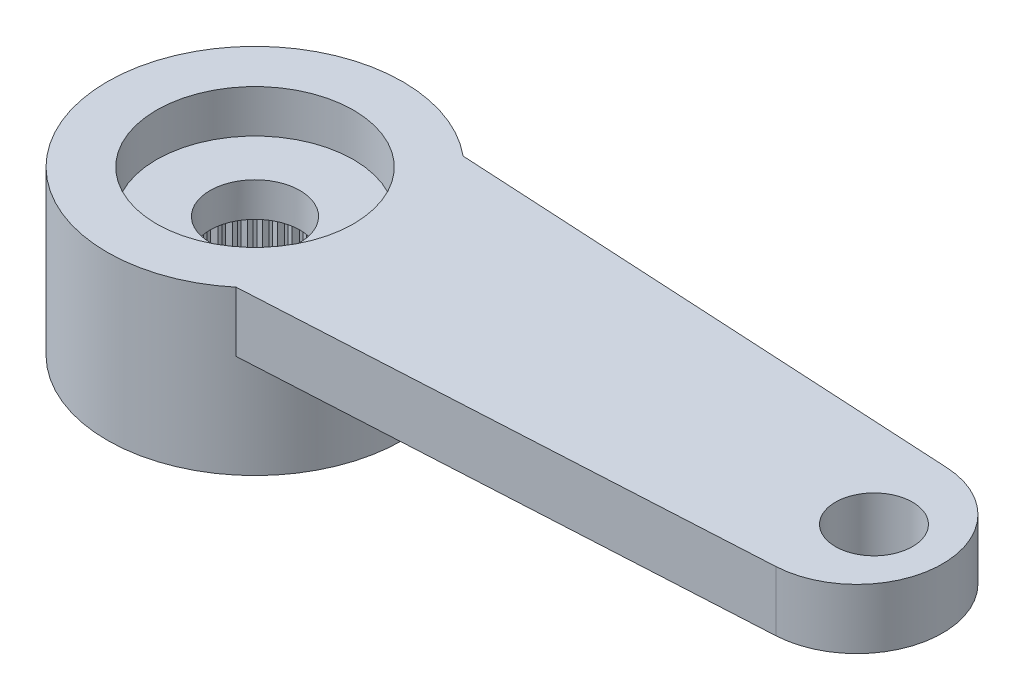
SolidWorks part; units mm, degrees
ref_plane "Front Plane" through (0, 0, 0) normal (0, 0, 1) x (1, 0, 0)
ref_plane "Top Plane" through (0, 0, 0) normal (0, 1, 0) x (1, 0, 0)
ref_plane "Right Plane" through (0, 0, 0) normal (1, 0, 0) x (0, 0, -1)
sketch "Sketch1" plane through (0, 0, 0) normal (0, 1, 0) x (1, 0, 0)
  line L0 (2.2091, -2.65) -> (14.1591, -1.997)
  line L1 (14.1591, 1.997) -> (2.2091, 2.65)
  line L2 (-2.2091, 2.65) -> (-14.1591, 1.997)
  line L3 (-14.1591, -1.997) -> (-2.2091, -2.65)
  arc A0 (-2.2091, -2.65) -> (2.2091, -2.65) centre (0, 0) ccw
  arc A1 (14.1591, -1.997) -> (14.1591, 1.997) centre (14.05, 0) ccw
  arc A2 (2.2091, 2.65) -> (-2.2091, 2.65) centre (0, 0) ccw
  arc A3 (-14.1591, 1.997) -> (-14.1591, -1.997) centre (-14.05, 0) ccw
extrude "Boss-Extrude1" add sketch "Sketch1" against normal blind 1.4
sketch "Sketch2" plane through (0, -1.4, 0) normal (0, -1, 0) x (1, 0, 0)
  circle A0 centre (0, 0) radius 3.45
extrude "Boss-Extrude2" add sketch "Sketch2" along normal blind 2.4
sketch "Sketch3" plane through (0, -3.8, 0) normal (0, -1, 0) x (1, 0, 0)
  line L0 (-0.161, 2.4698) -> (-0.2483, 2.362)
  line L1 (-0.2483, 2.362) -> (-0.356, 2.4493)
  line L2 (-0.4183, 2.4394) -> (-0.4938, 2.3231)
  line L3 (-0.4938, 2.3231) -> (-0.6101, 2.3986)
  line L4 (-0.671, 2.3823) -> (-0.7339, 2.2588)
  line L5 (-0.7339, 2.2588) -> (-0.8575, 2.3217)
  line L6 (-0.9163, 2.2991) -> (-0.966, 2.1697)
  line L7 (-0.966, 2.1697) -> (-1.0955, 2.2194)
  line L8 (-1.1516, 2.1908) -> (-1.1875, 2.0568)
  line L9 (-1.1875, 2.0568) -> (-1.3214, 2.0927)
  line L10 (-1.3743, 2.0584) -> (-1.396, 1.9214)
  line L11 (-1.396, 1.9214) -> (-1.533, 1.9431)
  line L12 (-1.5819, 1.9035) -> (-1.5892, 1.765)
  line L13 (-1.5892, 1.765) -> (-1.7277, 1.7722)
  line L14 (-1.7722, 1.7277) -> (-1.765, 1.5892)
  line L15 (-1.765, 1.5892) -> (-1.9035, 1.5819)
  line L16 (-1.9431, 1.533) -> (-1.9214, 1.396)
  line L17 (-1.9214, 1.396) -> (-2.0584, 1.3743)
  line L18 (-2.0927, 1.3214) -> (-2.0568, 1.1875)
  line L19 (-2.0568, 1.1875) -> (-2.1908, 1.1516)
  line L20 (-2.2194, 1.0955) -> (-2.1697, 0.966)
  line L21 (-2.1697, 0.966) -> (-2.2991, 0.9163)
  line L22 (-2.3217, 0.8575) -> (-2.2588, 0.7339)
  line L23 (-2.2588, 0.7339) -> (-2.3823, 0.671)
  line L24 (-2.3986, 0.6101) -> (-2.3231, 0.4938)
  line L25 (-2.3231, 0.4938) -> (-2.4394, 0.4183)
  line L26 (-2.4493, 0.356) -> (-2.362, 0.2483)
  line L27 (-2.362, 0.2483) -> (-2.4698, 0.161)
  line L28 (-2.4731, 0.0981) -> (-2.375, 0)
  line L29 (-2.375, 0) -> (-2.4731, -0.0981)
  line L30 (-2.4698, -0.161) -> (-2.362, -0.2483)
  line L31 (-2.362, -0.2483) -> (-2.4493, -0.356)
  line L32 (-2.4394, -0.4183) -> (-2.3231, -0.4938)
  line L33 (-2.3231, -0.4938) -> (-2.3986, -0.6101)
  line L34 (-2.3823, -0.671) -> (-2.2588, -0.7339)
  line L35 (-2.2588, -0.7339) -> (-2.3217, -0.8575)
  line L36 (-2.2991, -0.9163) -> (-2.1697, -0.966)
  line L37 (-2.1697, -0.966) -> (-2.2194, -1.0955)
  line L38 (-2.1908, -1.1516) -> (-2.0568, -1.1875)
  line L39 (-2.0568, -1.1875) -> (-2.0927, -1.3214)
  line L40 (-2.0584, -1.3743) -> (-1.9214, -1.396)
  line L41 (-1.9214, -1.396) -> (-1.9431, -1.533)
  line L42 (-1.9035, -1.5819) -> (-1.765, -1.5892)
  line L43 (-1.765, -1.5892) -> (-1.7722, -1.7277)
  line L44 (-1.7277, -1.7722) -> (-1.5892, -1.765)
  line L45 (-1.5892, -1.765) -> (-1.5819, -1.9035)
  line L46 (-1.533, -1.9431) -> (-1.396, -1.9214)
  line L47 (-1.396, -1.9214) -> (-1.3743, -2.0584)
  line L48 (-1.3214, -2.0927) -> (-1.1875, -2.0568)
  line L49 (-1.1875, -2.0568) -> (-1.1516, -2.1908)
  line L50 (-1.0955, -2.2194) -> (-0.966, -2.1697)
  line L51 (-0.966, -2.1697) -> (-0.9163, -2.2991)
  line L52 (-0.8575, -2.3217) -> (-0.7339, -2.2588)
  line L53 (-0.7339, -2.2588) -> (-0.671, -2.3823)
  line L54 (-0.6101, -2.3986) -> (-0.4938, -2.3231)
  line L55 (-0.4938, -2.3231) -> (-0.4183, -2.4394)
  line L56 (-0.356, -2.4493) -> (-0.2483, -2.362)
  line L57 (-0.2483, -2.362) -> (-0.161, -2.4698)
  line L58 (-0.0981, -2.4731) -> (0, -2.375)
  line L59 (0, -2.375) -> (0.0981, -2.4731)
  line L60 (0.161, -2.4698) -> (0.2483, -2.362)
  line L61 (0.2483, -2.362) -> (0.356, -2.4493)
  line L62 (0.4183, -2.4394) -> (0.4938, -2.3231)
  line L63 (0.4938, -2.3231) -> (0.6101, -2.3986)
  line L64 (0.671, -2.3823) -> (0.7339, -2.2588)
  line L65 (0.7339, -2.2588) -> (0.8575, -2.3217)
  line L66 (0.9163, -2.2991) -> (0.966, -2.1697)
  line L67 (0.966, -2.1697) -> (1.0955, -2.2194)
  line L68 (1.1516, -2.1908) -> (1.1875, -2.0568)
  line L69 (1.1875, -2.0568) -> (1.3214, -2.0927)
  line L70 (1.3743, -2.0584) -> (1.396, -1.9214)
  line L71 (1.396, -1.9214) -> (1.533, -1.9431)
  line L72 (1.5819, -1.9035) -> (1.5892, -1.765)
  line L73 (1.5892, -1.765) -> (1.7277, -1.7722)
  line L74 (1.7722, -1.7277) -> (1.765, -1.5892)
  line L75 (1.765, -1.5892) -> (1.9035, -1.5819)
  line L76 (1.9431, -1.533) -> (1.9214, -1.396)
  line L77 (1.9214, -1.396) -> (2.0584, -1.3743)
  line L78 (2.0927, -1.3214) -> (2.0568, -1.1875)
  line L79 (2.0568, -1.1875) -> (2.1908, -1.1516)
  line L80 (2.2194, -1.0955) -> (2.1697, -0.966)
  line L81 (2.1697, -0.966) -> (2.2991, -0.9163)
  line L82 (2.3217, -0.8575) -> (2.2588, -0.7339)
  line L83 (2.2588, -0.7339) -> (2.3823, -0.671)
  line L84 (2.3986, -0.6101) -> (2.3231, -0.4938)
  line L85 (2.3231, -0.4938) -> (2.4394, -0.4183)
  line L86 (2.4493, -0.356) -> (2.362, -0.2483)
  line L87 (2.362, -0.2483) -> (2.4698, -0.161)
  line L88 (2.4731, -0.0981) -> (2.375, 0)
  line L89 (2.375, 0) -> (2.4731, 0.0981)
  line L90 (2.4698, 0.161) -> (2.362, 0.2483)
  line L91 (2.362, 0.2483) -> (2.4493, 0.356)
  line L92 (2.4394, 0.4183) -> (2.3231, 0.4938)
  line L93 (2.3231, 0.4938) -> (2.3986, 0.6101)
  line L94 (2.3823, 0.671) -> (2.2588, 0.7339)
  line L95 (2.2588, 0.7339) -> (2.3217, 0.8575)
  line L96 (2.2991, 0.9163) -> (2.1697, 0.966)
  line L97 (2.1697, 0.966) -> (2.2194, 1.0955)
  line L98 (2.1908, 1.1516) -> (2.0568, 1.1875)
  line L99 (2.0568, 1.1875) -> (2.0927, 1.3214)
  line L100 (2.0584, 1.3743) -> (1.9214, 1.396)
  line L101 (1.9214, 1.396) -> (1.9431, 1.533)
  line L102 (1.9035, 1.5819) -> (1.765, 1.5892)
  line L103 (1.765, 1.5892) -> (1.7722, 1.7277)
  line L104 (1.7277, 1.7722) -> (1.5892, 1.765)
  line L105 (1.5892, 1.765) -> (1.5819, 1.9035)
  line L106 (1.533, 1.9431) -> (1.396, 1.9214)
  line L107 (1.396, 1.9214) -> (1.3743, 2.0584)
  line L108 (1.3214, 2.0927) -> (1.1875, 2.0568)
  line L109 (1.1875, 2.0568) -> (1.1516, 2.1908)
  line L110 (1.0955, 2.2194) -> (0.966, 2.1697)
  line L111 (0.966, 2.1697) -> (0.9163, 2.2991)
  line L112 (0.8575, 2.3217) -> (0.7339, 2.2588)
  line L113 (0.7339, 2.2588) -> (0.671, 2.3823)
  line L114 (0.6101, 2.3986) -> (0.4938, 2.3231)
  line L115 (0.4938, 2.3231) -> (0.4183, 2.4394)
  line L116 (0.356, 2.4493) -> (0.2483, 2.362)
  line L117 (0.2483, 2.362) -> (0.161, 2.4698)
  line L118 (0.0981, 2.4731) -> (0, 2.375)
  line L119 (0, 2.375) -> (-0.0981, 2.4731)
  arc A0 (-0.0981, 2.4731) -> (-0.161, 2.4698) centre (0, 0) ccw
  arc A1 (-0.356, 2.4493) -> (-0.4183, 2.4394) centre (0, 0) ccw
  arc A2 (-0.6101, 2.3986) -> (-0.671, 2.3823) centre (0, 0) ccw
  arc A3 (-0.8575, 2.3217) -> (-0.9163, 2.2991) centre (0, 0) ccw
  arc A4 (-1.0955, 2.2194) -> (-1.1516, 2.1908) centre (0, 0) ccw
  arc A5 (-1.3214, 2.0927) -> (-1.3743, 2.0584) centre (0, 0) ccw
  arc A6 (-1.533, 1.9431) -> (-1.5819, 1.9035) centre (0, 0) ccw
  arc A7 (-1.7277, 1.7722) -> (-1.7722, 1.7277) centre (0, 0) ccw
  arc A8 (-1.9035, 1.5819) -> (-1.9431, 1.533) centre (0, 0) ccw
  arc A9 (-2.0584, 1.3743) -> (-2.0927, 1.3214) centre (0, 0) ccw
  arc A10 (-2.1908, 1.1516) -> (-2.2194, 1.0955) centre (0, 0) ccw
  arc A11 (-2.2991, 0.9163) -> (-2.3217, 0.8575) centre (0, 0) ccw
  arc A12 (-2.3823, 0.671) -> (-2.3986, 0.6101) centre (0, 0) ccw
  arc A13 (-2.4394, 0.4183) -> (-2.4493, 0.356) centre (0, 0) ccw
  arc A14 (-2.4698, 0.161) -> (-2.4731, 0.0981) centre (0, 0) ccw
  arc A15 (-2.4731, -0.0981) -> (-2.4698, -0.161) centre (0, 0) ccw
  arc A16 (-2.4493, -0.356) -> (-2.4394, -0.4183) centre (0, 0) ccw
  arc A17 (-2.3986, -0.6101) -> (-2.3823, -0.671) centre (0, 0) ccw
  arc A18 (-2.3217, -0.8575) -> (-2.2991, -0.9163) centre (0, 0) ccw
  arc A19 (-2.2194, -1.0955) -> (-2.1908, -1.1516) centre (0, 0) ccw
  arc A20 (-2.0927, -1.3214) -> (-2.0584, -1.3743) centre (0, 0) ccw
  arc A21 (-1.9431, -1.533) -> (-1.9035, -1.5819) centre (0, 0) ccw
  arc A22 (-1.7722, -1.7277) -> (-1.7277, -1.7722) centre (0, 0) ccw
  arc A23 (-1.5819, -1.9035) -> (-1.533, -1.9431) centre (0, 0) ccw
  arc A24 (-1.3743, -2.0584) -> (-1.3214, -2.0927) centre (0, 0) ccw
  arc A25 (-1.1516, -2.1908) -> (-1.0955, -2.2194) centre (0, 0) ccw
  arc A26 (-0.9163, -2.2991) -> (-0.8575, -2.3217) centre (0, 0) ccw
  arc A27 (-0.671, -2.3823) -> (-0.6101, -2.3986) centre (0, 0) ccw
  arc A28 (-0.4183, -2.4394) -> (-0.356, -2.4493) centre (0, 0) ccw
  arc A29 (-0.161, -2.4698) -> (-0.0981, -2.4731) centre (0, 0) ccw
  arc A30 (0.0981, -2.4731) -> (0.161, -2.4698) centre (0, 0) ccw
  arc A31 (0.356, -2.4493) -> (0.4183, -2.4394) centre (0, 0) ccw
  arc A32 (0.6101, -2.3986) -> (0.671, -2.3823) centre (0, 0) ccw
  arc A33 (0.8575, -2.3217) -> (0.9163, -2.2991) centre (0, 0) ccw
  arc A34 (1.0955, -2.2194) -> (1.1516, -2.1908) centre (0, 0) ccw
  arc A35 (1.3214, -2.0927) -> (1.3743, -2.0584) centre (0, 0) ccw
  arc A36 (1.533, -1.9431) -> (1.5819, -1.9035) centre (0, 0) ccw
  arc A37 (1.7277, -1.7722) -> (1.7722, -1.7277) centre (0, 0) ccw
  arc A38 (1.9035, -1.5819) -> (1.9431, -1.533) centre (0, 0) ccw
  arc A39 (2.0584, -1.3743) -> (2.0927, -1.3214) centre (0, 0) ccw
  arc A40 (2.1908, -1.1516) -> (2.2194, -1.0955) centre (0, 0) ccw
  arc A41 (2.2991, -0.9163) -> (2.3217, -0.8575) centre (0, 0) ccw
  arc A42 (2.3823, -0.671) -> (2.3986, -0.6101) centre (0, 0) ccw
  arc A43 (2.4394, -0.4183) -> (2.4493, -0.356) centre (0, 0) ccw
  arc A44 (2.4698, -0.161) -> (2.4731, -0.0981) centre (0, 0) ccw
  arc A45 (2.4731, 0.0981) -> (2.4698, 0.161) centre (0, 0) ccw
  arc A46 (2.4493, 0.356) -> (2.4394, 0.4183) centre (0, 0) ccw
  arc A47 (2.3986, 0.6101) -> (2.3823, 0.671) centre (0, 0) ccw
  arc A48 (2.3217, 0.8575) -> (2.2991, 0.9163) centre (0, 0) ccw
  arc A49 (2.2194, 1.0955) -> (2.1908, 1.1516) centre (0, 0) ccw
  arc A50 (2.0927, 1.3214) -> (2.0584, 1.3743) centre (0, 0) ccw
  arc A51 (1.9431, 1.533) -> (1.9035, 1.5819) centre (0, 0) ccw
  arc A52 (1.7722, 1.7277) -> (1.7277, 1.7722) centre (0, 0) ccw
  arc A53 (1.5819, 1.9035) -> (1.533, 1.9431) centre (0, 0) ccw
  arc A54 (1.3743, 2.0584) -> (1.3214, 2.0927) centre (0, 0) ccw
  arc A55 (1.1516, 2.1908) -> (1.0955, 2.2194) centre (0, 0) ccw
  arc A56 (0.9163, 2.2991) -> (0.8575, 2.3217) centre (0, 0) ccw
  arc A57 (0.671, 2.3823) -> (0.6101, 2.3986) centre (0, 0) ccw
  arc A58 (0.4183, 2.4394) -> (0.356, 2.4493) centre (0, 0) ccw
  arc A59 (0.161, 2.4698) -> (0.0981, 2.4731) centre (0, 0) ccw
extrude "Cut-Extrude1" cut sketch "Sketch3" against normal blind 2
hole_wizard "Hole1" positions "Sketch5" profile "Sketch4" legacy
sketch "Sketch5" plane through (0, 0, 0) normal (0, 1, 0) x (1, 0, 0)
  point P0 (0, 0)
sketch "Sketch4" plane through (0, 0, 0) normal (1, 0, 0) x (0, 0, 1)
  line L0 (0, 0) -> (0, 3.8)
  line L1 (0, 3.8) -> (1.05, 3.8)
  line L2 (1.05, 3.8) -> (1.05, 1)
  line L3 (1.05, 1) -> (2.3, 1)
  line L4 (2.3, 1) -> (2.3, 0)
  line L5 (2.3, 0) -> (0, 0)
  line L6 (0, 110) -> (0, -10) construction
  dimension "Diameter" = 2.1
  dimension "Depth" = 3.8
  dimension "C-Bore Diameter" = 4.6
  dimension "C-Bore Depth" = 1
sketch "Sketch6" plane through (0, 0, 0) normal (0, 1, 0) x (1, 0, 0)
  line L3 (-14.1591, -1.997) -> (-2.2091, -2.65)
  line L4 (-2.2091, 2.65) -> (-2.124, 2.7652)
  line L5 (-2.124, 2.7652) -> (-14.05, 2.65)
  line L8 (-14.05, 2.65) -> (-16.05, 2.65)
  line L9 (-16.05, 2.65) -> (-16.05, 0)
  arc A0 (-2.2091, 2.65) -> (-2.2091, -2.65) centre (0, 0) ccw
  arc A2 (-16.05, 0) -> (-14.1591, -1.997) centre (-14.05, 0) ccw
extrude "Cut-Extrude2" cut sketch "Sketch6" against normal blind 10
sketch "Sketch7" plane through (0, 0, 0) normal (0, 1, 0) x (1, 0, 0)
  line L0 (0, 0) -> (14.45, 0) construction
  circle A0 centre (14.45, 0) radius 0.9
extrude "Cut-Extrude3" cut sketch "Sketch7" against normal blind 10
